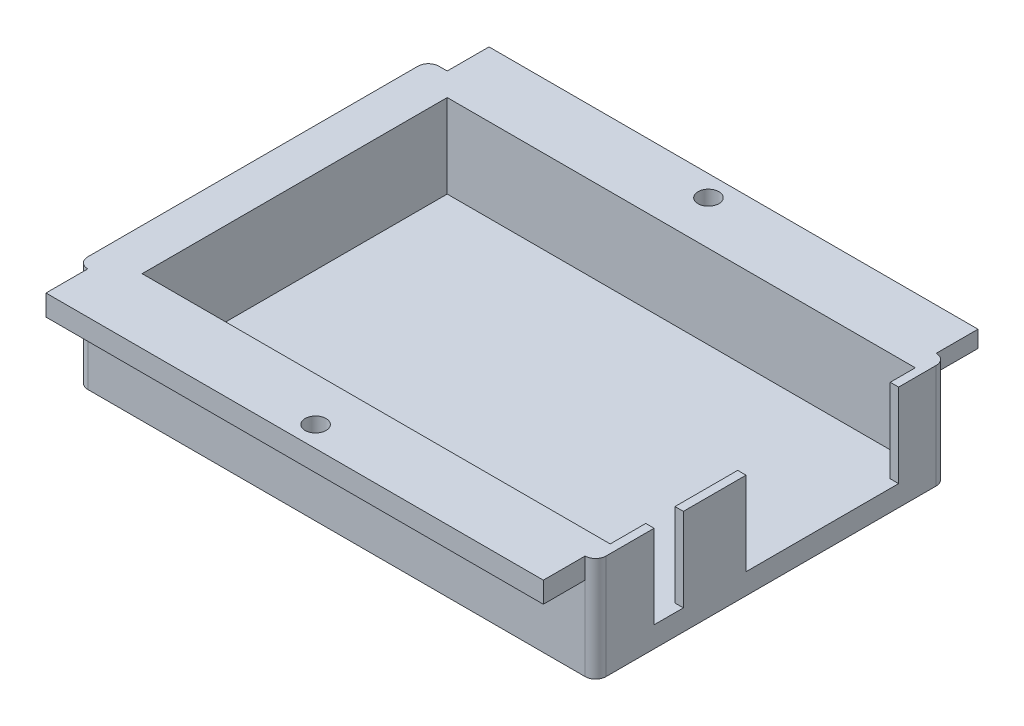
SolidWorks part; units mm, degrees
ref_plane "Front Plane" through (0, 0, 0) normal (0, 0, 1) x (1, 0, 0)
ref_plane "Top Plane" through (0, 0, 0) normal (0, 1, 0) x (1, 0, 0)
ref_plane "Right Plane" through (0, 0, 0) normal (1, 0, 0) x (0, 0, -1)
sketch "Sketch1" plane through (0, 0, 0) normal (0, 1, 0) x (1, 0, 0)
  line L1 (-62, -42) -> (62, -42)
  line L2 (-62, -42) -> (-62, 42)
  line L3 (-62, 42) -> (62, 42)
  line L4 (62, -42) -> (62, 42)
  line L5 (-62, -42) -> (62, 42) construction
  line L6 (-62, 42) -> (62, -42) construction
  point P0 (0, 0)
  dimension "D1" = 124
  dimension "D2" = 84
extrude "Boss-Extrude1" add sketch "Sketch1" along normal blind 25
sketch "Sketch2" plane through (0, 25, 0) normal (0, 1, 0) x (1, 0, 0)
  line L0 (-52, 36.5) -> (-52, -36.5)
  line L1 (-52, -36.5) -> (60, -36.5)
  line L3 (-52, 36.5) -> (60, 36.5)
  line L4 (60, -36.5) -> (60, 36.5)
  line L5 (62, -42) -> (62, 42) construction
  line L6 (0, -36.5) -> (0, 36.5) construction
  point P0 (0, 0)
  dimension "D1" = 112
  dimension "D2" = 73
  dimension "D3" = 2
extrude "Cut-Extrude1" cut sketch "Sketch2" against normal blind 20
sketch "Sketch3" plane through (0, 25, 0) normal (0, 1, 0) x (1, 0, 0)
  line L0 (-52, -36.5) -> (60, -36.5) construction
  line L1 (-62, -42) -> (62, -42) construction
  line L2 (60, -28) -> (62, -28)
  line L3 (60, -36.5) -> (60, 36.5) construction
  line L4 (62, -42) -> (62, 42) construction
  line L5 (62, -28) -> (62, -42)
  line L6 (62, -42) -> (60, -42)
  line L7 (60, -42) -> (60, -28)
  line L8 (62, 42) -> (62, 30.5)
  line L9 (62, 30.5) -> (60, 30.5)
  line L10 (60, -36.5) -> (60, 36.5) construction
  line L11 (60, 30.5) -> (60, 42)
  line L12 (62, 42) -> (-62, 42) construction
  line L13 (60, 42) -> (62, 42)
  dimension "D1" = 5.5
  dimension "D2" = 14
  dimension "D3" = 11.5
sketch "Sketch4" plane through (0, 25, 0) normal (0, 1, 0) x (1, 0, 0)
  line L0 (60, -28) -> (62, -28)
  line L1 (62, -28) -> (62, -21)
  line L2 (62, -42) -> (62, 42) construction
  line L3 (62, -21) -> (60, -21)
  line L4 (60, -36.5) -> (60, 36.5) construction
  line L5 (60, -21) -> (60, -28)
  line L6 (62, -42) -> (60, -42) construction
  line L7 (60, 30.5) -> (62, 30.5)
  line L8 (62, 30.5) -> (62, -6)
  line L9 (62, -6) -> (60, -6)
  line L10 (60, -36.5) -> (60, 36.5) construction
  line L11 (60, -6) -> (60, 30.5)
  dimension "D1" = 21
  dimension "D2" = 15
extrude "Cut-Extrude2" cut sketch "Sketch4" against normal blind 20
fillet "Fillet1" radius 2.5 4 edges at (-62, 12.5, -42) (62, 12.5, -42) (62, 12.5, 42) (-62, 12.5, 42)
sketch "Sketch5" plane through (0, 0, 42) normal (0, 0, 1) x (1, 0, 0)
  line L0 (59.5, 0) -> (59.5, 25) construction
  line L1 (-59.5, 25) -> (59.5, 25)
  line L2 (-59.5, 25) -> (-59.5, 20)
  line L3 (-59.5, 20) -> (59.5, 20)
  line L4 (59.5, 25) -> (59.5, 20)
  dimension "D1" = 5
extrude "Boss-Extrude2" add sketch "Sketch5" along normal blind 10
sketch "Sketch6" plane through (0, 0, -42) normal (0, 0, -1) x (-1, 0, 0)
  line L1 (-59.5, 25) -> (57.5, 25)
  line L2 (-59.5, 25) -> (-59.5, 21)
  line L3 (-59.5, 21) -> (57.5, 21)
  line L4 (57.5, 25) -> (57.5, 21)
  dimension "D1" = 4
  dimension "D2" = 117
extrude "Boss-Extrude3" add sketch "Sketch6" along normal blind 10
sketch "Sketch7" plane through (0, 25, 0) normal (0, 1, 0) x (1, 0, 0)
  line L0 (-57.5, 52) -> (59.5, 52) construction
  line L1 (59.5, -52) -> (-59.5, -52) construction
  circle A0 centre (0, 47) radius 2.5
  circle A1 centre (0, -47) radius 2.5
  point P8 (0, -52)
  dimension "D1" = 5
  dimension "D2" = 5
extrude "Cut-Extrude3" cut sketch "Sketch7" against normal through all
